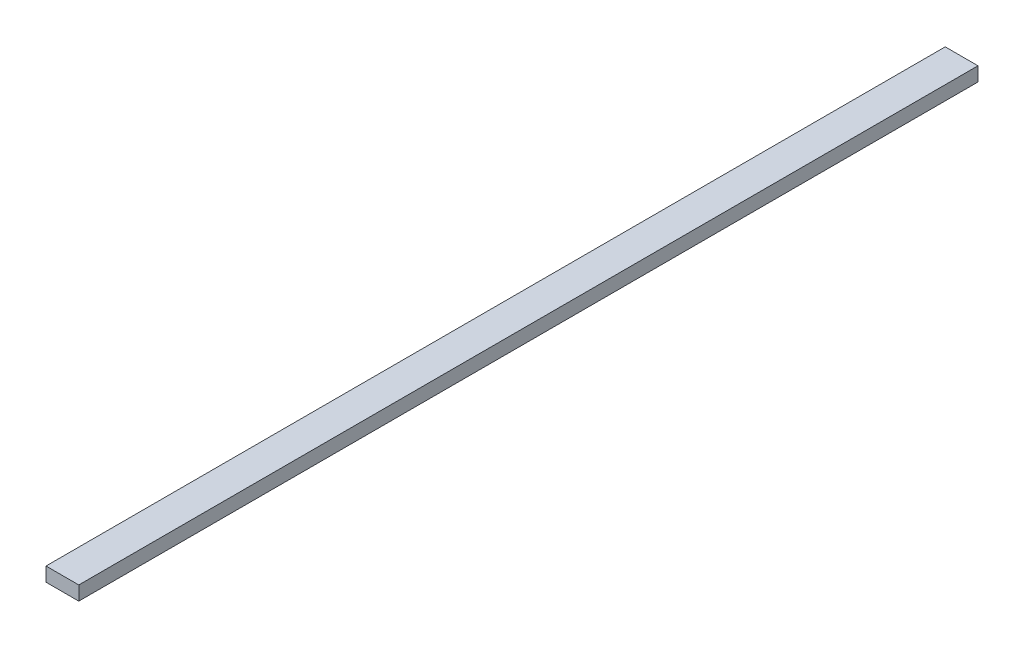
SolidWorks part; units mm, degrees
ref_plane "Front Plane" through (0, 0, 0) normal (0, 0, 1) x (1, 0, 0)
ref_plane "Top Plane" through (0, 0, 0) normal (0, 1, 0) x (1, 0, 0)
ref_plane "Right Plane" through (0, 0, 0) normal (1, 0, 0) x (0, 0, -1)
sketch "Sketch1" plane through (0, 0, 0) normal (0, 0, 1) x (1, 0, 0)
  line L1 (0, 0) -> (88.9, 0)
  line L2 (0, 0) -> (0, 38.1)
  line L3 (0, 38.1) -> (88.9, 38.1)
  line L4 (88.9, 0) -> (88.9, 38.1)
  dimension "D1" = 88.9
  dimension "D2" = 38.1
extrude "Boss-Extrude1" add sketch "Sketch1" along normal blind 2438.4
